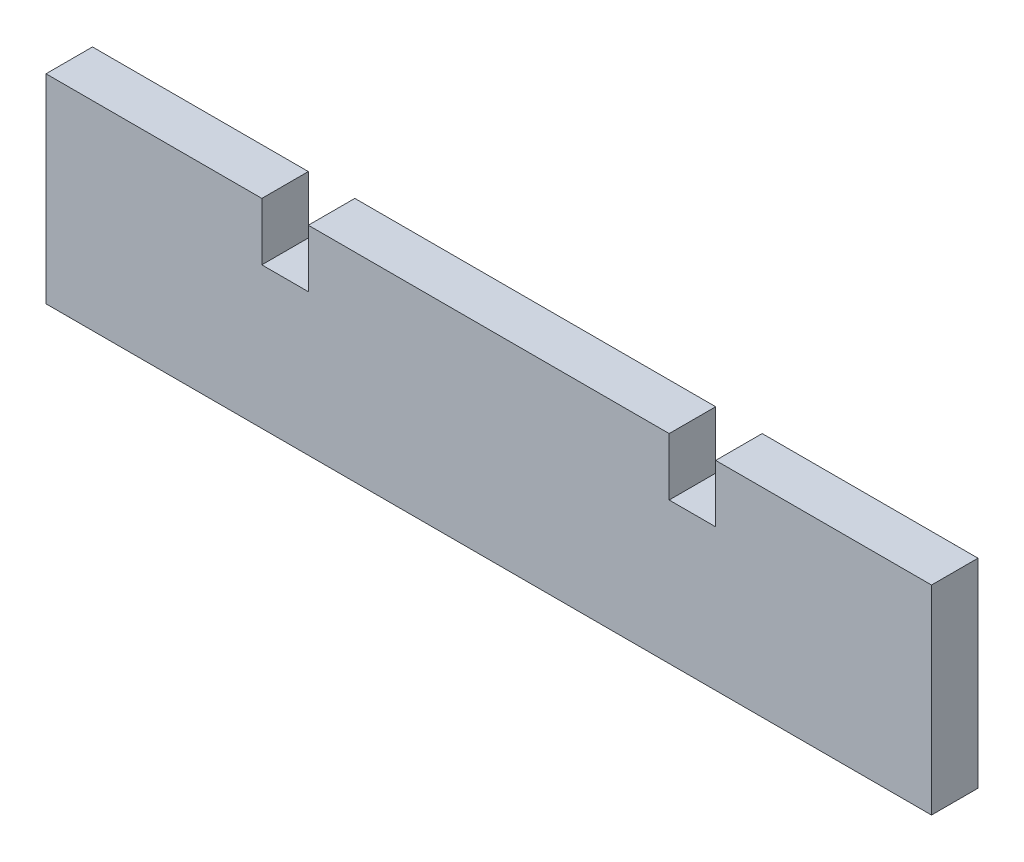
SolidWorks part; units mm, degrees
ref_plane "Front Plane" through (0, 0, 0) normal (0, 0, 1) x (1, 0, 0)
ref_plane "Top Plane" through (0, 0, 0) normal (0, 1, 0) x (1, 0, 0)
ref_plane "Right Plane" through (0, 0, 0) normal (1, 0, 0) x (0, 0, -1)
sketch "Sketch1" plane through (0, 0, 0) normal (0, 0, 1) x (1, 0, 0)
  line L1 (-60.394, -18.3718) -> (41.206, -18.3718)
  line L2 (-60.394, -18.3718) -> (-60.394, -41.2318)
  line L3 (-60.394, -41.2318) -> (41.206, -41.2318)
  line L4 (41.206, -18.3718) -> (41.206, -41.2318)
  dimension "D1" = 101.6
  dimension "D2" = 22.86
extrude "Boss-Extrude1" add sketch "Sketch1" along normal blind 5.334
sketch "Sketch2" plane through (0, 0, 5.334) normal (0, 0, 1) x (1, 0, 0)
  line L0 (-9.594, -18.3718) -> (-9.594, -41.2318) construction
  line L1 (41.206, -18.3718) -> (-60.394, -18.3718) construction
  line L2 (-60.394, -41.2318) -> (41.206, -41.2318) construction
  line L3 (-35.629, -18.3718) -> (-35.629, -24.9758)
  line L4 (11.107, -18.3718) -> (16.441, -18.3718)
  line L5 (11.107, -18.3718) -> (11.107, -24.9758)
  line L6 (11.107, -24.9758) -> (16.441, -24.9758)
  line L7 (16.441, -18.3718) -> (16.441, -24.9758)
  line L8 (-30.295, -24.9758) -> (-35.629, -24.9758)
  line L9 (-30.295, -18.3718) -> (-30.295, -24.9758)
  line L10 (-30.295, -18.3718) -> (-35.629, -18.3718)
  dimension "D1" = 20.701
  dimension "D2" = 5.334
  dimension "D3" = 6.604
extrude "Cut-Extrude1" cut sketch "Sketch2" against normal through all
equation "\"MDF\"= .21in"
equation "\"Foamcore\"= .13in"
equation "\"Gmaterial\"= \"MDF\""
equation "\"D1@Boss-Extrude1\"=\"MDF\""
equation "\"D2@Sketch2\"=\"MDF\""
